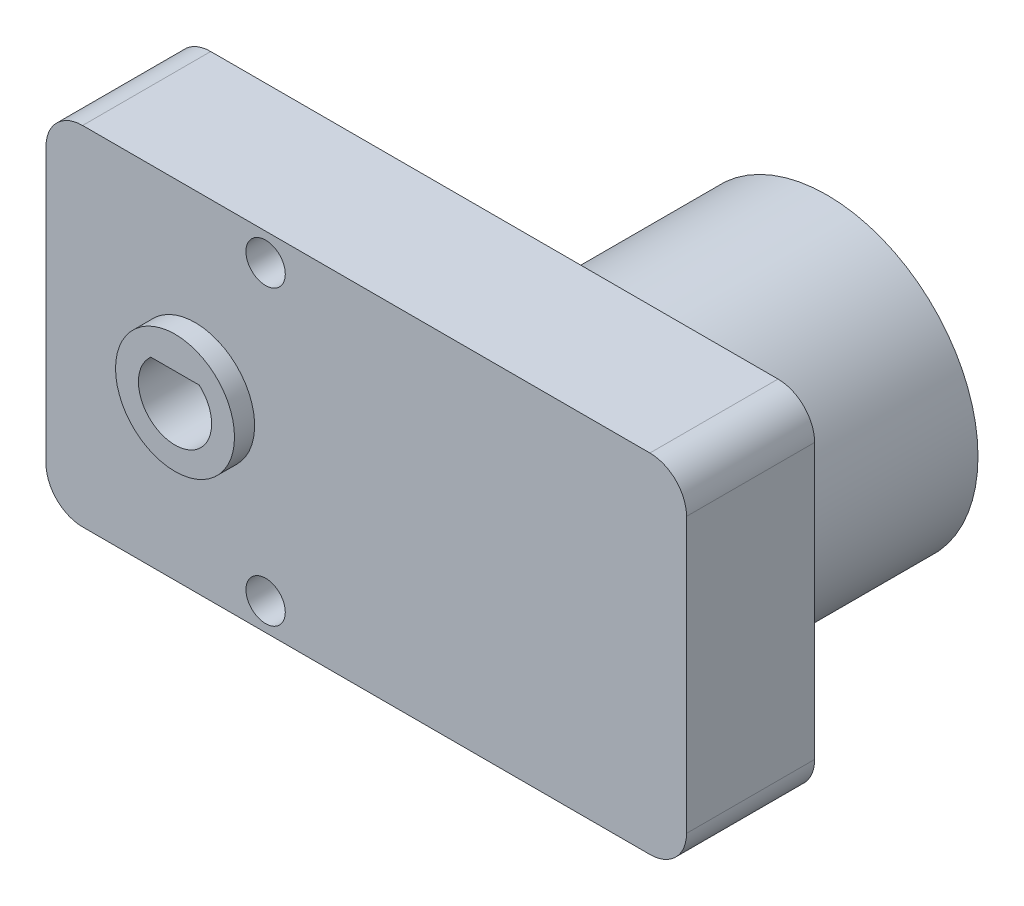
SolidWorks part; units mm, degrees
ref_plane "Front Plane" through (0, 0, 0) normal (0, 0, 1) x (1, 0, 0)
ref_plane "Top Plane" through (0, 0, 0) normal (0, 1, 0) x (1, 0, 0)
ref_plane "Right Plane" through (0, 0, 0) normal (1, 0, 0) x (0, 0, -1)
sketch "Sketch1" plane through (0, 0, 0) normal (0, 0, 1) x (1, 0, 0)
  line L0 (24, 38) -> (24, 0) construction
  line L1 (0, 0) -> (70, 0)
  line L2 (0, 0) -> (0, 38)
  line L3 (0, 38) -> (70, 38)
  line L4 (70, 0) -> (70, 38)
  line L5 (16.3, 38) -> (16.3, 0) construction
  line L6 (13.6542, 22) -> (18.9458, 22)
  circle A0 centre (24, 35) radius 2.15
  circle A1 centre (24, 3) radius 2.15
  circle A2 centre (16.3, 19) radius 4 construction
  arc A3 (13.6542, 22) -> (18.9458, 22) centre (16.3, 19) ccw
  point P16 (24, 19)
  dimension "D4" = 16
  dimension "D6" = 4.3
  dimension "D8" = 3
  dimension "D9" = 4
  dimension "D1" = 70
  dimension "D2" = 38
  dimension "D3" = 46
  dimension "D5" = 16
  dimension "D7" = 16.3
extrude "Boss-Extrude1" add sketch "Sketch1" along normal blind 14
fillet "Fillet1" radius 4 4 edges at (0, 0, 7) (70, 0, 7) (0, 38, 7) (70, 38, 7)
sketch "Sketch2" plane through (0, 0, 0) normal (0, 0, -1) x (-1, 0, 0)
  line L0 (-70, 19) -> (0, 19) construction
  line L1 (-70, 4) -> (-70, 34) construction
  line L2 (0, 34) -> (0, 4) construction
  line L3 (-66, 38) -> (-4, 38) construction
  circle A0 centre (-48.7538, 19) radius 16.5
  circle A1 centre (-57, 35) radius 1.5 construction
  dimension "D1" = 33
  dimension "D5" = 3
  dimension "D3" = 3
  dimension "D4" = 13
extrude "Boss-Extrude2" add sketch "Sketch2" along normal blind 22.6
sketch "Sketch3" plane through (0, 0, 0) normal (0, 0, -1) x (-1, 0, 0)
  line L0 (-18.9458, 22) -> (-13.6542, 22)
  circle A0 centre (-16.3, 19) radius 6.5
  arc A1 (-18.9458, 22) -> (-13.6542, 22) centre (-16.3, 19) ccw
  arc A2 (-18.9458, 22) -> (-13.6542, 22) centre (-16.3, 19) ccw construction
  dimension "D1" = 13
extrude "Boss-Extrude3" add sketch "Sketch3" along normal blind 2.2
sketch "Sketch4" plane through (0, 0, 14) normal (0, 0, 1) x (1, 0, 0)
  line L0 (13.6542, 22) -> (18.9458, 22)
  circle A0 centre (16.3, 19) radius 6.5
  arc A1 (13.6542, 22) -> (18.9458, 22) centre (16.3, 19) ccw
  arc A2 (13.6542, 22) -> (18.9458, 22) centre (16.3, 19) ccw construction
  dimension "D1" = 13
extrude "Boss-Extrude4" add sketch "Sketch4" along normal blind 2.2
